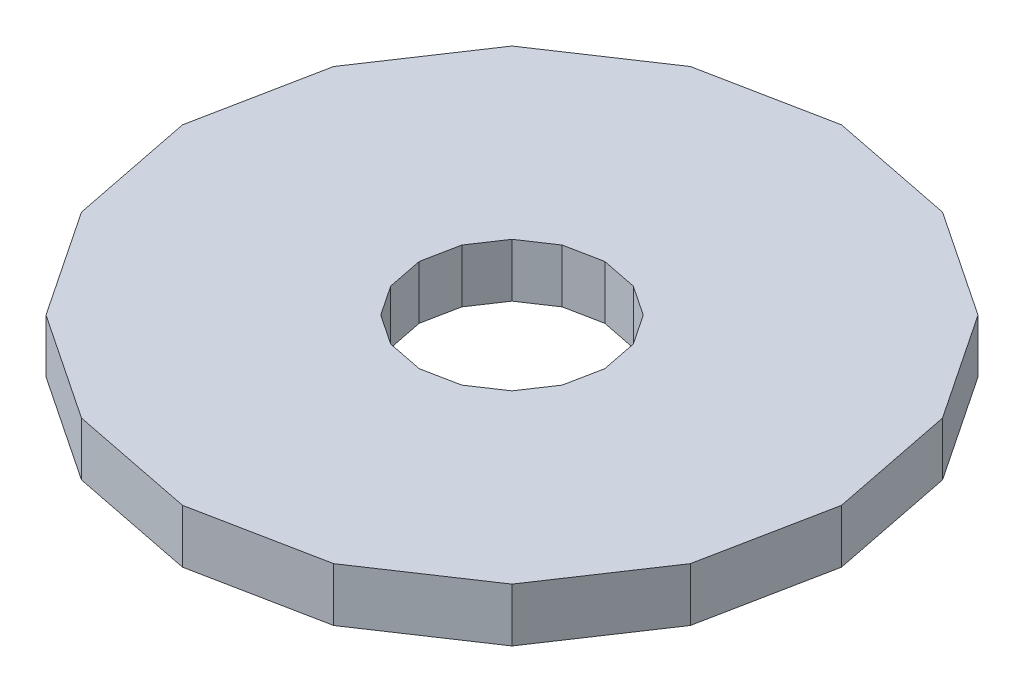
SolidWorks part; units mm, degrees
ref_plane "Front Plane" through (0, 0, 0) normal (0, 0, 1) x (1, 0, 0)
ref_plane "Top Plane" through (0, 0, 0) normal (0, 1, 0) x (1, 0, 0)
ref_plane "Right Plane" through (0, 0, 0) normal (1, 0, 0) x (0, 0, -1)
sketch "Sketch1" plane through (0, 0, 0) normal (0, 1, 0) x (1, 0, 0)
  line L1 (33.0092, 0) -> (30.4966, 12.6321)
  line L2 (30.4966, 12.6321) -> (23.3411, 23.3411)
  line L3 (23.3411, 23.3411) -> (12.6321, 30.4966)
  line L4 (12.6321, 30.4966) -> (0, 33.0092)
  line L5 (0, 33.0092) -> (-12.6321, 30.4966)
  line L6 (-12.6321, 30.4966) -> (-23.3411, 23.3411)
  line L7 (-23.3411, 23.3411) -> (-30.4966, 12.6321)
  line L8 (-30.4966, 12.6321) -> (-33.0092, 0)
  line L9 (-33.0092, 0) -> (-30.4966, -12.6321)
  line L10 (-30.4966, -12.6321) -> (-23.3411, -23.3411)
  line L11 (-23.3411, -23.3411) -> (-12.6321, -30.4966)
  line L12 (-12.6321, -30.4966) -> (0, -33.0092)
  line L13 (0, -33.0092) -> (12.6321, -30.4966)
  line L14 (12.6321, -30.4966) -> (23.3411, -23.3411)
  line L15 (23.3411, -23.3411) -> (30.4966, -12.6321)
  line L16 (30.4966, -12.6321) -> (33.0092, 0)
  line L17 (117.1765, 0) -> (108.257, 44.8415)
  line L18 (108.257, 44.8415) -> (82.8563, 82.8563)
  line L19 (82.8563, 82.8563) -> (44.8415, 108.257)
  line L20 (44.8415, 108.257) -> (0, 117.1765)
  line L21 (0, 117.1765) -> (-44.8415, 108.257)
  line L22 (-44.8415, 108.257) -> (-82.8563, 82.8563)
  line L23 (-82.8563, 82.8563) -> (-108.257, 44.8415)
  line L24 (-108.257, 44.8415) -> (-117.1765, 0)
  line L25 (-117.1765, 0) -> (-108.257, -44.8415)
  line L26 (-108.257, -44.8415) -> (-82.8563, -82.8563)
  line L27 (-82.8563, -82.8563) -> (-44.8415, -108.257)
  line L28 (-44.8415, -108.257) -> (0, -117.1765)
  line L29 (0, -117.1765) -> (44.8415, -108.257)
  line L30 (44.8415, -108.257) -> (82.8563, -82.8563)
  line L31 (82.8563, -82.8563) -> (108.257, -44.8415)
  line L32 (108.257, -44.8415) -> (117.1765, 0)
  circle A0 centre (0, 0) radius 32.375 construction
  circle A1 centre (0, 0) radius 114.925 construction
  dimension "D1" = 45.72
  dimension "D2" = 82.55
extrude "Boss-Extrude1" add sketch "Sketch1" along normal blind 19.05
